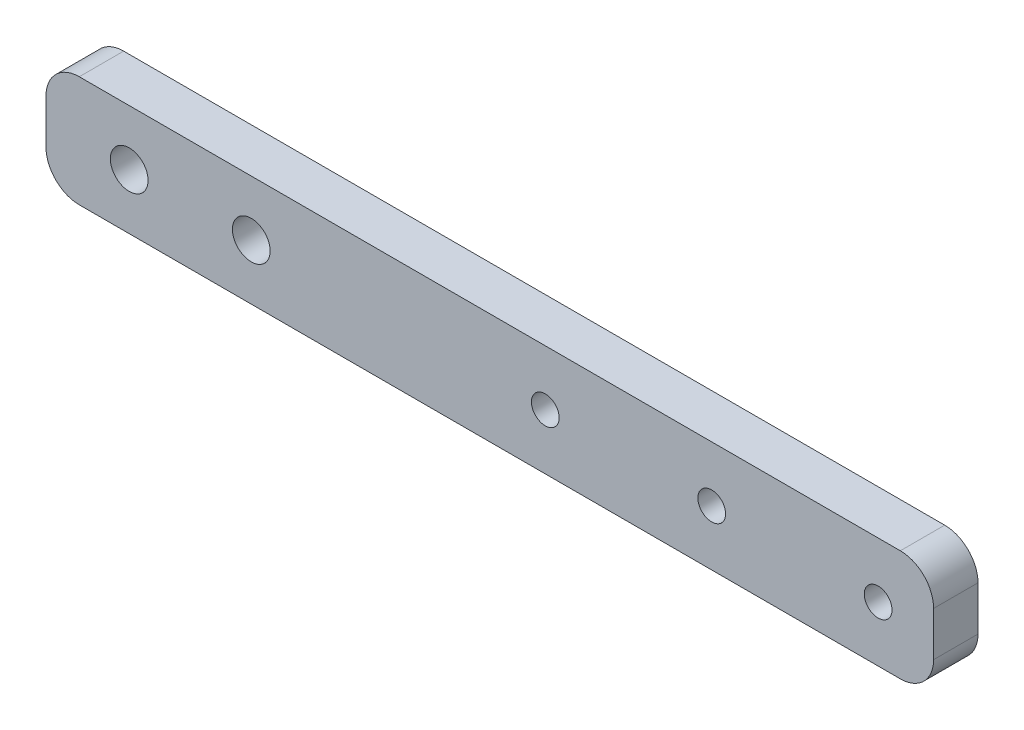
SolidWorks part; units mm, degrees
ref_plane "前视基准面" through (0, 0, 0) normal (0, 0, 1) x (1, 0, 0)
ref_plane "上视基准面" through (0, 0, 0) normal (0, 1, 0) x (1, 0, 0)
ref_plane "右视基准面" through (0, 0, 0) normal (1, 0, 0) x (0, 0, -1)
sketch "草图1" plane through (0, 0, 0) normal (0, 0, 1) x (1, 0, 0)
  line L0 (80, 5) -> (0, 5) construction
  line L1 (0, 0) -> (80, 0)
  line L2 (0, 0) -> (0, 10)
  line L3 (0, 10) -> (80, 10)
  line L4 (80, 0) -> (80, 10)
  circle A0 centre (45, 5) radius 1.25
  circle A1 centre (60, 5) radius 1.25
  circle A2 centre (75, 5) radius 1.25
  circle A3 centre (7.5, 5) radius 1.7
  circle A4 centre (18.5, 5) radius 1.7
  dimension "D3" = 2.5
  dimension "D6" = 5
  dimension "D7" = 3.4
  dimension "D8" = 3.4
  dimension "D9" = 11
  dimension "D10" = 26.5
  dimension "D1" = 80
  dimension "D2" = 10
  dimension "D4" = 15
  dimension "D5" = 15
extrude "凸台-拉伸1" add sketch "草图1" along normal blind 4
fillet "圆角1" radius 3 4 edges at (80, 0, 2) (80, 10, 2) (0, 0, 2) (0, 10, 2)
sketch "草图2" plane through (0, 0, 4) normal (0, 0, 1) x (1, 0, 0)
  line L0 (7.5, 5) -> (18.5, 5)
  line L1 (13, 5) -> (13, -46.2799) construction
